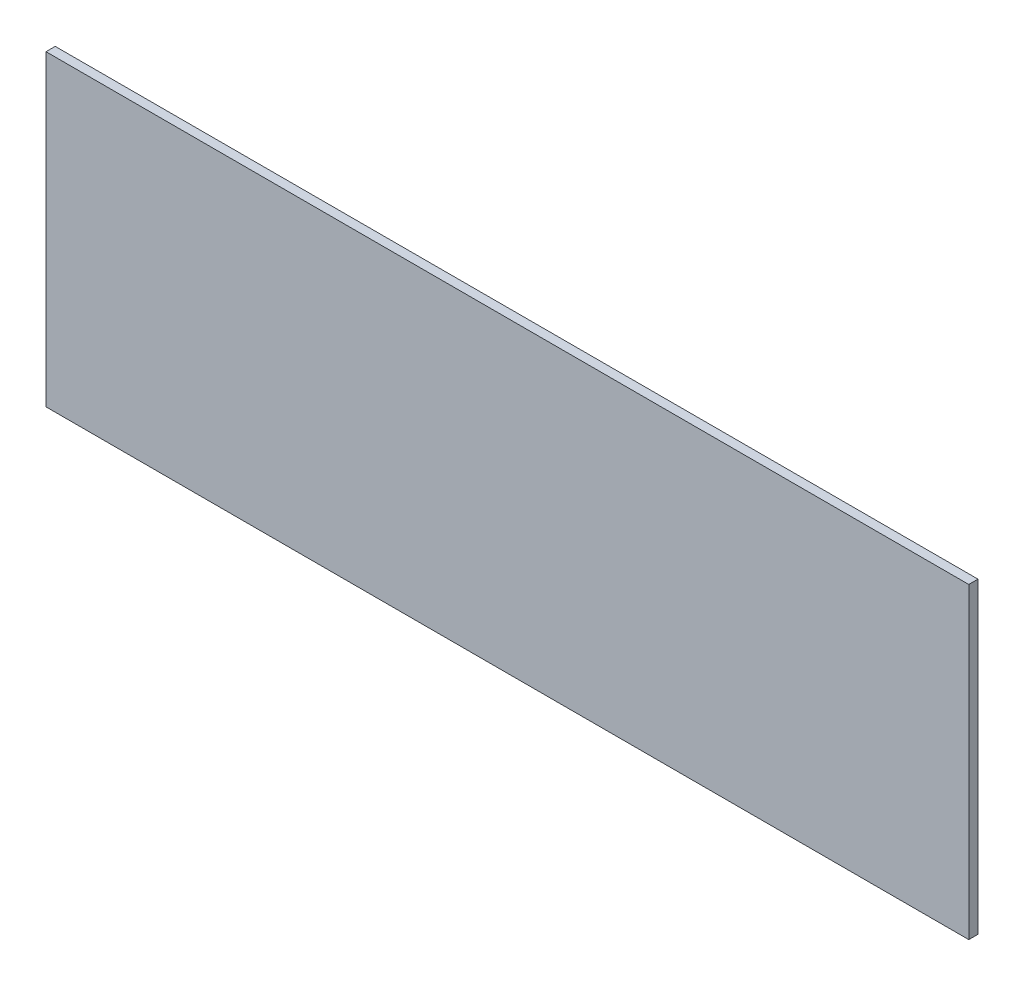
SolidWorks part; units mm, degrees
ref_plane "Front Plane" through (0, 0, 0) normal (0, 0, 1) x (1, 0, 0)
ref_plane "Top Plane" through (0, 0, 0) normal (0, 1, 0) x (1, 0, 0)
ref_plane "Right Plane" through (0, 0, 0) normal (1, 0, 0) x (0, 0, -1)
sketch "Sketch1" plane through (0, 0, 0) normal (0, 0, 1) x (1, 0, 0)
  line L1 (0, 0) -> (300, 0)
  line L2 (0, 0) -> (0, 100)
  line L3 (0, 100) -> (300, 100)
  line L4 (300, 0) -> (300, 100)
  dimension "D1" = 300
  dimension "D2" = 100
extrude "Boss-Extrude1" add sketch "Sketch1" along normal blind 3
